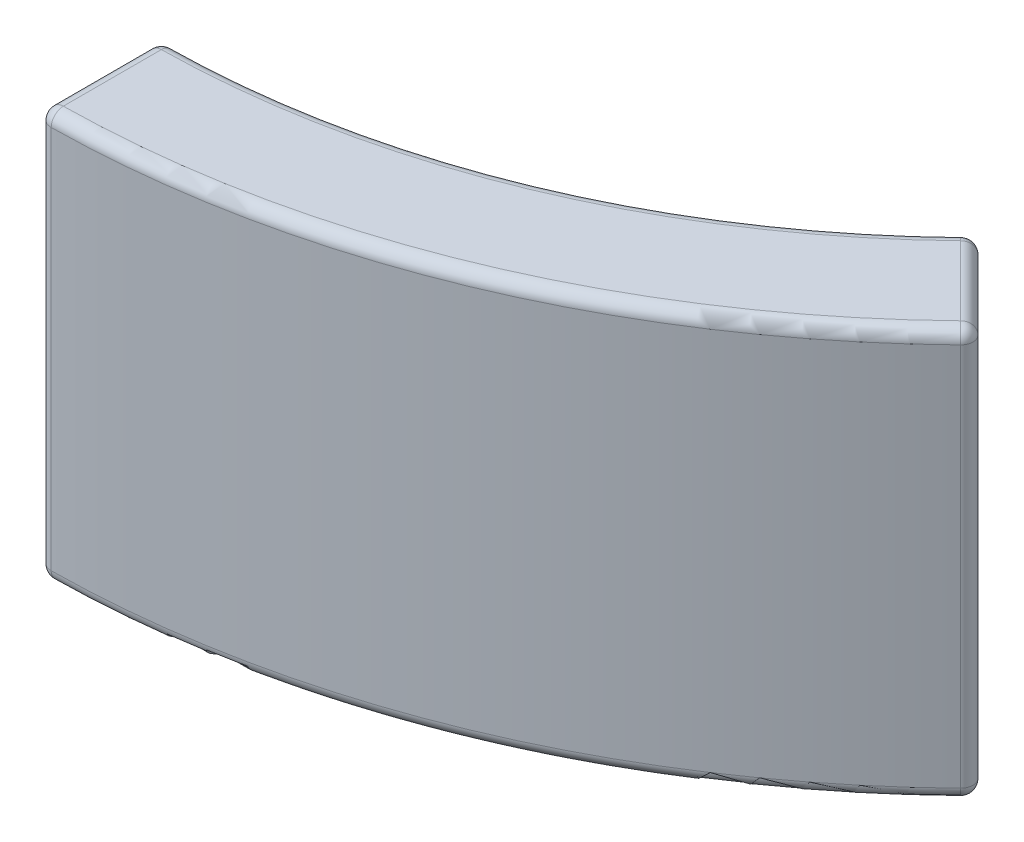
SolidWorks part; units mm, degrees
ref_plane "Front Plane" through (0, 0, 0) normal (0, 0, 1) x (1, 0, 0)
ref_plane "Top Plane" through (0, 0, 0) normal (0, 1, 0) x (1, 0, 0)
ref_plane "Right Plane" through (0, 0, 0) normal (1, 0, 0) x (0, 0, -1)
sketch "Sketch1" plane through (0, 0, 0) normal (0, 1, 0) x (1, 0, 0)
  line L0 (14.1421, -14.1421) -> (16.2635, -16.2635)
  line L1 (0, -20) -> (0, -23)
  arc A0 (0, -23) -> (16.2635, -16.2635) centre (0, 0) ccw
  arc A1 (0, -20) -> (14.1421, -14.1421) centre (0, 0) ccw
  point P7 (0, 0)
  point P8 (0, 0)
  point P9 (16.0196, -16.6112)
  point P10 (0, 0)
  point P11 (0, 0)
  point P12 (0, 0)
  point P13 (0, 0)
  point P14 (0, 0)
  point P15 (0, 0)
  point P16 (0, 0)
  point P17 (15.5766, -15.5656)
  point P18 (16.2689, -16.258)
  point P19 (0, 0)
  point P20 (0, 0)
  point P21 (14.6393, -16.7234)
  point P22 (15.742, -15.29)
  point P23 (0, 0)
  point P24 (0, 0)
  point P25 (16.1855, -16.341)
  point P26 (0, 0)
  point P27 (0, 0)
  point P28 (0, 0)
  dimension "D2" = 20
  dimension "D3" = 23
  dimension "D6" = 3
  dimension "D1" = 3
  dimension "D4" = 45
  dimension "D5" = 45
extrude "Boss-Extrude1" add sketch "Sketch1" along normal blind 10
fillet "Fillet1" radius 0.3 12 edges at (15.2028, 0, 15.2028) (14.1421, 5, 14.1421) (7.6537, 0, 18.4776) (0, 5, 20) (0, 0, 21.5) (15.2028, 10, 15.2028) (0, 10, 21.5) (7.6537, 10, 18.4776) (0, 5, 23) (8.8017, 10, 21.2492) (16.2635, 5, 16.2635) (8.8017, 0, 21.2492)
